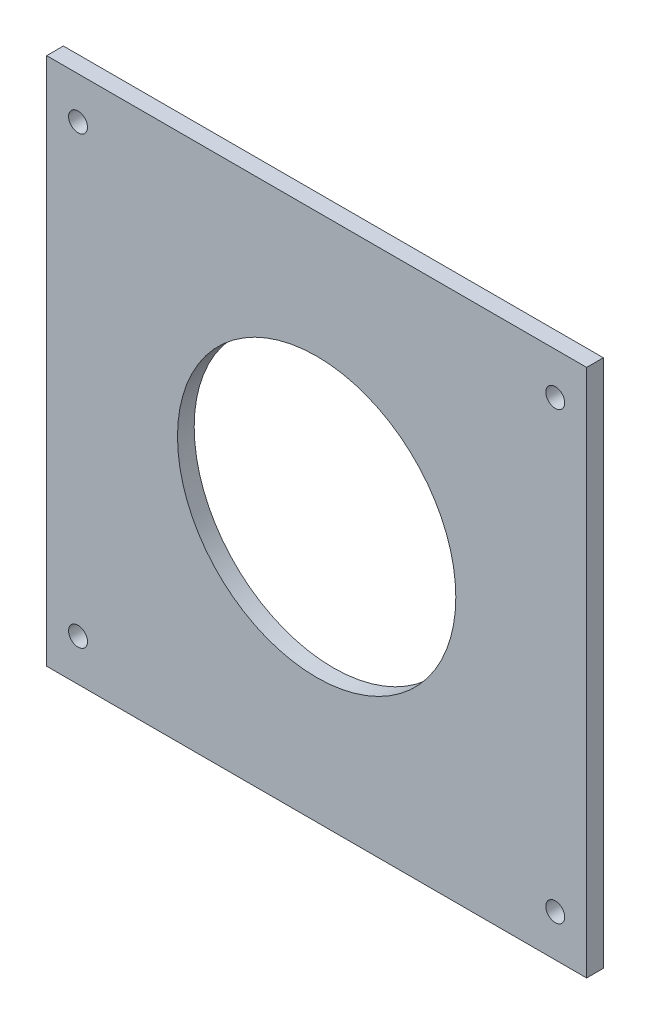
SolidWorks part; units mm, degrees
material "6061-T6 (SS)"
ref_plane "Front Plane" through (0, 0, 0) normal (0, 0, 1) x (1, 0, 0)
ref_plane "Top Plane" through (0, 0, 0) normal (0, 1, 0) x (1, 0, 0)
ref_plane "Right Plane" through (0, 0, 0) normal (1, 0, 0) x (0, 0, -1)
sketch "Body sketch" plane through (0, 0, 0) normal (0, 0, 1) x (1, 0, 0)
  line L1 (0, 0) -> (97, 0)
  line L2 (0, 0) -> (0, 95)
  line L3 (0, 95) -> (97, 95)
  line L4 (97, 0) -> (97, 95)
extrude "Body" add sketch "Body sketch" along normal blind 3
sketch "Holes sketch" plane through (0, 0, 0) normal (0, 0, 1) x (1, 0, 0)
  circle A0 centre (5.635, 7.495) radius 1.7
  circle A1 centre (91.365, 7.495) radius 1.7
  circle A2 centre (5.635, 87.505) radius 1.7
  circle A3 centre (91.365, 87.505) radius 1.7
  circle A4 centre (48.5, 47.5) radius 25
extrude "Holes" cut sketch "Holes sketch" against normal through all and the other way through all
